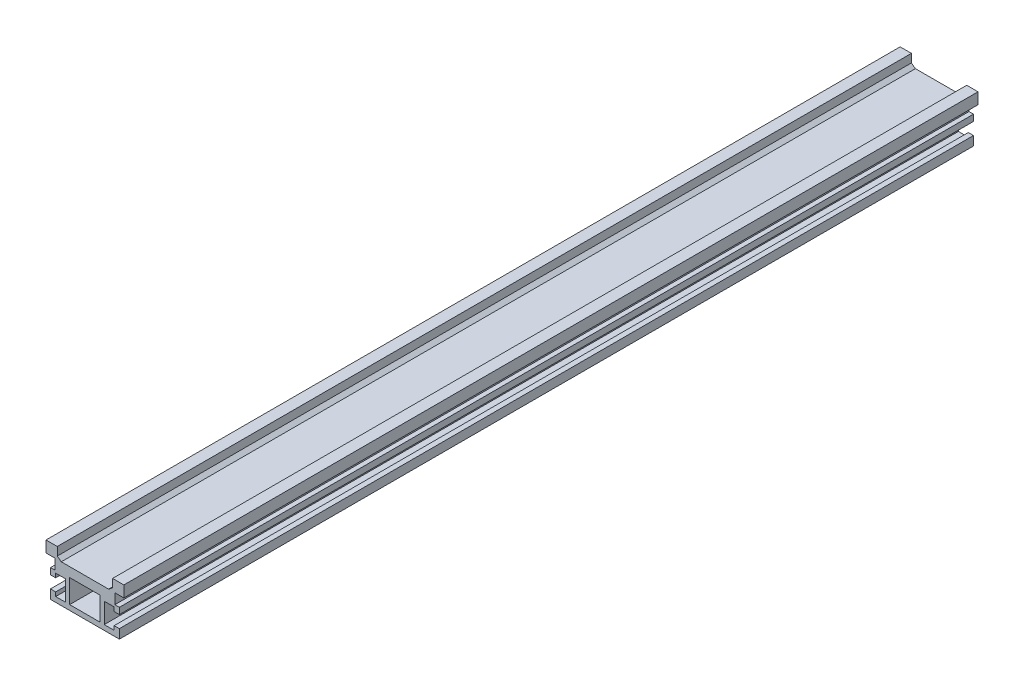
SolidWorks part; units mm, degrees
ref_plane "Front Plane" through (0, 0, 0) normal (0, 0, 1) x (1, 0, 0)
ref_plane "Top Plane" through (0, 0, 0) normal (0, 1, 0) x (1, 0, 0)
ref_plane "Right Plane" through (0, 0, 0) normal (1, 0, 0) x (0, 0, -1)
sketch "Sketch2" plane through (0, 0, 0) normal (0, 0, 1) x (1, 0, 0)
  line L1 (0, 0) -> (34.55, 0)
  line L2 (0, 0) -> (0, 21.85)
  line L3 (0, 21.85) -> (34.55, 21.85)
  line L4 (34.55, 0) -> (34.55, 21.85)
  dimension "D1" = 34.55
  dimension "D2" = 21.85
extrude "Boss-Extrude1" add sketch "Sketch2" against normal blind 379
sketch "Sketch3" plane through (0, 0, 0) normal (0, 0, 1) x (1, 0, 0)
  line L0 (34.55, 21.85) -> (0, 21.85) construction
  line L1 (34.55, 0) -> (34.55, 21.85) construction
  line L2 (17.275, 21.85) -> (29.55, 21.85)
  line L3 (17.275, 21.85) -> (17.275, 16.85)
  line L4 (17.275, 16.85) -> (29.55, 16.85)
  line L5 (29.55, 21.85) -> (29.55, 16.85)
  line L7 (0, 21.85) -> (0, 0) construction
  line L8 (17.275, 16.85) -> (27.775, 16.85)
  line L9 (27.775, 16.85) -> (34.55, 21.85)
  line L10 (34.55, 16.85) -> (30.55, 16.85)
  line L11 (30.55, 16.85) -> (30.55, 12.25)
  line L12 (30.55, 12.25) -> (32.55, 12.25)
  line L13 (32.55, 12.25) -> (32.55, 9.45)
  line L14 (32.55, 9.45) -> (30.25, 9.45)
  line L15 (30.25, 9.45) -> (30.25, 11.25)
  line L16 (30.25, 11.25) -> (25.85, 11.25)
  line L17 (25.85, 11.25) -> (25.85, 2.25)
  line L18 (25.85, 2.25) -> (30.25, 2.25)
  line L19 (30.25, 2.25) -> (30.25, 4.05)
  line L20 (30.25, 4.05) -> (32.55, 4.05)
  line L21 (32.55, 4.05) -> (32.55, 0)
  line L22 (0, 0) -> (34.55, 0) construction
  line M16 (0, 0) -> (34.55, 0)
  line M17 (34.55, 0) -> (34.55, 21.85)
  line M18 (34.55, 21.85) -> (0, 21.85)
  dimension "D1" = 5
  dimension "D2" = 5
  dimension "D3" = 17.275
  dimension "D4" = 10.5
  dimension "D5" = 4
  dimension "D6" = 4.6
  dimension "D7" = 2
  dimension "D8" = 2.8
  dimension "D9" = 2.3
  dimension "D10" = 1.8
  dimension "D11" = 4.4
  dimension "D12" = 9
  dimension "D13" = 1.8
extrude "Cut-Extrude1" cut sketch "Sketch3" against normal blind 379 contours L4 L9 L5 L3 M18 | L20 L21 L10 L11 L12 L13 L14 L15 L16 L17 L18 L19 M16 M17
ref_plane "Plane2" through (17.275, 0, 0) normal (1, 0, 0) x (0, 0, -1)
mirror "Mirror1" about plane through (17.275, 0, 0) normal (1, 0, 0) of "Cut-Extrude1"
sketch "Sketch5" plane through (0, 0, 0) normal (0, 0, 1) x (1, 0, 0)
  line L1 (10.5, 2.25) -> (24.05, 2.25)
  line L2 (10.5, 2.25) -> (10.5, 12.65)
  line L3 (10.5, 12.65) -> (24.05, 12.65)
  line L4 (24.05, 2.25) -> (24.05, 12.65)
  line L5 (30.25, 2.25) -> (30.25, 0)
  line L6 (2, 0) -> (32.55, 0) construction
  line L7 (25.85, 11.25) -> (25.85, 2.25) construction
  line L8 (8.7, 11.25) -> (8.7, 2.25) construction
  dimension "D1" = 2.25
  dimension "D2" = 1.8
  dimension "D3" = 1.8
  dimension "D4" = 10.4
extrude "Cut-Extrude2" cut sketch "Sketch5" against normal blind 379 contours L1 L4 L3 L2
sketch "Sketch6" plane through (0, 0, 0) normal (0, -1, 0) x (1, 0, 0)
  line L0 (17.275, -379) -> (17.275, -359)
  line L2 (2, -379) -> (32.55, -379) construction
  line L3 (17.275, -359) -> (17.275, -185.4)
  line L4 (17.275, -185.4) -> (17.275, -158.7333)
  dimension "D1" = 20
  dimension "D2" = 193.6
  dimension "D3" = 26.6667
hole_wizard "Ø5.0mm Dowel Hole2" positions "Sketch9" profile "Sketch10" hole size "Ø5.0" standard "ANSI Metric"
sketch "Sketch9" plane through (0, 0, 0) normal (0, -1, 0) x (-1, 0, 0)
  line L0 (-17.275, 185.4) -> (-17.275, 158.7333)
  point P0 (-17.275, 359)
  point P3 (-17.275, 185.4)
  point P8 (-17.275, 158.7333)
  dimension "D1" = 26.6667
sketch "Sketch10" plane through (17.275, 0, -359) normal (1, 0, 0) x (0, 0, -1)
  line L0 (0, 0) -> (0, 2.25)
  line L1 (0, 2.25) -> (2.5, 2.25)
  line L2 (2.5, 2.25) -> (2.5, 0)
  line L5 (2.5, 0) -> (0, 0)
  line L11 (0, -6.35) -> (0, 107.95) construction
  dimension "Thru Hole Dia." = 5
  dimension "Thru Hole Depth" = 2.25
